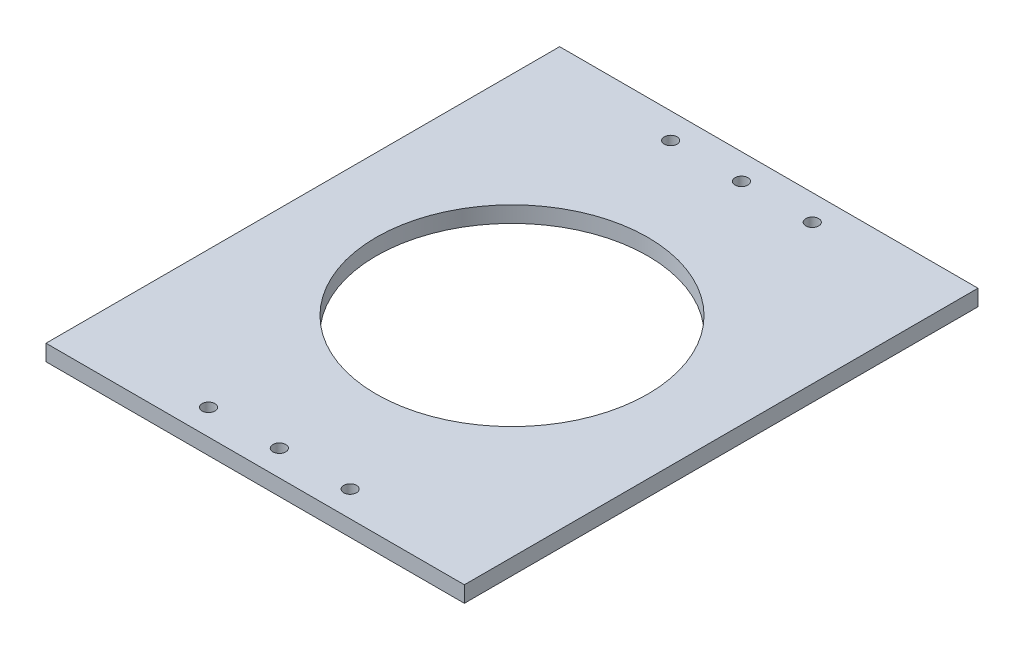
SolidWorks part; units mm, degrees
ref_plane "Front Plane" through (0, 0, 0) normal (0, 0, 1) x (1, 0, 0)
ref_plane "Top Plane" through (0, 0, 0) normal (0, 1, 0) x (1, 0, 0)
ref_plane "Right Plane" through (0, 0, 0) normal (1, 0, 0) x (0, 0, -1)
sketch "Sketch1" plane through (0, 0, 0) normal (0, 1, 0) x (1, 0, 0)
  line L0 (-276.663, 35.6247) -> (-130.5123, 35.6247) construction
  line L1 (-341.663, 115.4247) -> (-211.663, 115.4247)
  line L2 (-341.663, 115.4247) -> (-341.663, -44.1753)
  line L3 (-341.663, -44.1753) -> (-211.663, -44.1753)
  line L4 (-211.663, 115.4247) -> (-211.663, -44.1753)
  line L5 (-341.663, 115.4247) -> (-211.663, -44.1753) construction
  line L6 (-341.663, -44.1753) -> (-211.663, 115.4247) construction
  circle A0 centre (-276.663, 35.6247) radius 42.1979
  circle A1 centre (-299.163, 107.4247) radius 2
  circle A2 centre (-277.163, 107.4247) radius 2
  circle A3 centre (-255.163, 107.4247) radius 2
  circle A4 centre (-255.163, -36.1753) radius 2
  circle A5 centre (-277.163, -36.1753) radius 2
  circle A6 centre (-299.163, -36.1753) radius 2
  point P0 (-276.663, 35.6247)
  dimension "D1" = 159.6
  dimension "D2" = 130
extrude "Boss-Extrude1" add sketch "Sketch1" along normal blind 5
